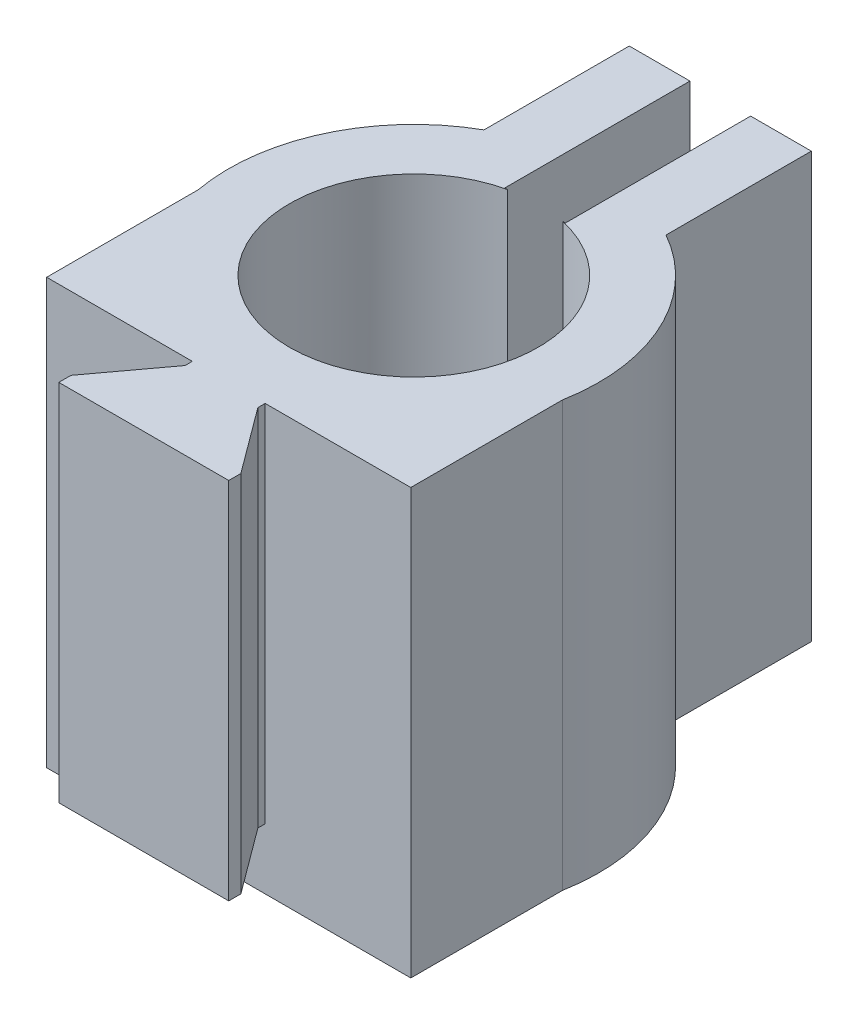
SolidWorks part; units mm, degrees
ref_plane "Piano frontale" through (0, 0, 0) normal (0, 0, 1) x (1, 0, 0)
ref_plane "Piano superiore" through (0, 0, 0) normal (0, 1, 0) x (1, 0, 0)
ref_plane "Piano destro" through (0, 0, 0) normal (1, 0, 0) x (0, 0, -1)
sketch "Schizzo1" plane through (0, 0, 0) normal (0, 1, 0) x (1, 0, 0)
  circle A0 centre (0, 0) radius 10.25
  circle A1 centre (0, 0) radius 15.25
  dimension "D1" = 20.5
  dimension "D2" = 5
extrude "Estrusione-Estrusione1" add sketch "Schizzo1" along normal blind 30
sketch "Schizzo4" plane through (0, 0, 0) normal (0, -1, 0) x (1, 0, 0)
  line L0 (0, 0) -> (0, -34.0018) construction
  line L1 (-7.5, -10.25) -> (7.5, -10.25)
  line L2 (-7.5, -10.25) -> (-7.5, -25.25)
  line L3 (-7.5, -25.25) -> (7.5, -25.25)
  line L4 (7.5, -10.25) -> (7.5, -25.25)
  circle A0 centre (0, 0) radius 10.25 construction
  dimension "D1" = 15
  dimension "D2" = 15
  dimension "D3" = 7.5
extrude "Estrusione-Estrusione2" add sketch "Schizzo4" against normal blind 30
sketch "Schizzo5" plane through (0, 0, 0) normal (0, -1, 0) x (1, 0, 0)
  line L0 (-7.5, -25.25) -> (7.5, -25.25) construction
  line L1 (-2.5, -25.25) -> (2.5, -25.25)
  line L2 (-2.5, -25.25) -> (-2.5, -9.992)
  line L3 (-2.5, -9.992) -> (2.5, -9.992)
  line L4 (2.5, -25.25) -> (2.5, -9.992)
  line L5 (-7.5, -13.2783) -> (-7.5, -25.25) construction
  dimension "D1" = 5
  dimension "D2" = 5
extrude "Taglio-Estrusione1" cut sketch "Schizzo5" against normal blind 30
sketch "Schizzo6" plane through (0, 30, 0) normal (0, 1, 0) x (1, 0, 0)
  line L0 (0, -15.25) -> (0, -10.25) construction
  line L1 (15, -15.25) -> (-15, -15.25)
  line L2 (15, -15.25) -> (15, -10.25) construction
  line L3 (15, -10.25) -> (-15, -10.25) construction
  line L4 (-15, -15.25) -> (-15, -10.25) construction
  line L5 (15.25, 0) -> (-15.25, 0) construction
  line L6 (0, -15.25) -> (0, 25.2037) construction
  line L7 (15, -15.25) -> (15, -2.75)
  line L8 (-15, -15.25) -> (-15, -2.75)
  line L9 (-3, -15.25) -> (-3, -15.85)
  line L10 (3, -15.25) -> (3, -15.85)
  line L14 (-7, -22.25) -> (-7, -21.25)
  line L15 (7, -22.25) -> (7, -21.25)
  line L16 (7, -21.25) -> (3, -15.85)
  line L17 (-3, -15.85) -> (-7, -21.25)
  line L18 (-7, -22.25) -> (7, -22.25)
  arc A0 (-7.5, 13.2783) -> (7.5, 13.2783) centre (0, 0) ccw construction
  arc A1 (-2.285, 9.992) -> (2.285, 9.992) centre (0, 0) ccw construction
  arc A2 (-15, -2.75) -> (15, -2.75) centre (0, 0) ccw
  dimension "D1" = 30
  dimension "D2" = 5
  dimension "D3" = 0.6
  dimension "D4" = 1
  dimension "D5" = 14
  dimension "D6" = 6
  dimension "D7" = 7
  dimension "D8" = 3
extrude "Estrusione-Estrusione3" add sketch "Schizzo6" against normal through all
sketch "Schizzo7" plane through (0, 0, 0) normal (0, -1, 0) x (1, 0, 0)
  line L0 (-15, 15.25) -> (15, 15.25)
  line L1 (15, 15.25) -> (15, 2.75)
  line L2 (-15, 15.25) -> (-15, 2.75)
  line L3 (-2.5, -9.992) -> (-2.5, -25.25)
  line L4 (-2.5, -25.25) -> (-7.5, -25.25)
  line L5 (-7.5, -25.25) -> (-7.5, -13.2783)
  line L6 (2.5, -9.992) -> (2.5, -25.25)
  line L7 (2.5, -25.25) -> (7.5, -25.25)
  line L8 (7.5, -25.25) -> (7.5, -13.2783)
  arc A0 (-7.5, -13.2783) -> (-15, 2.75) centre (0, 0) cw
  arc A1 (7.5, -13.2783) -> (15, 2.75) centre (0, 0) ccw
  arc A2 (2.5, -9.992) -> (-2.5, -9.992) centre (0, -0.0254) ccw
extrude "Estrusione-Estrusione4" add sketch "Schizzo7" along normal blind 5
